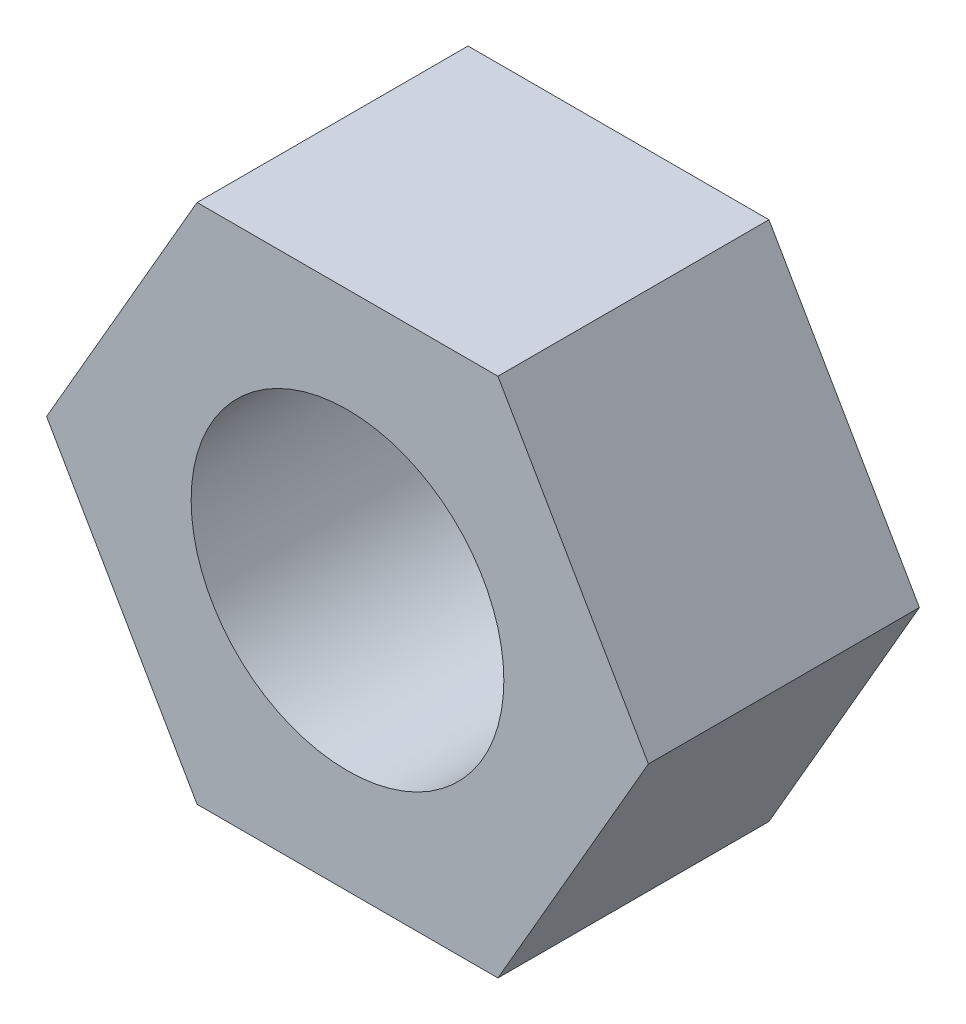
SolidWorks part; units mm, degrees
ref_plane "前视基准面" through (0, 0, 0) normal (0, 0, 1) x (1, 0, 0)
ref_plane "上视基准面" through (0, 0, 0) normal (0, 1, 0) x (1, 0, 0)
ref_plane "右视基准面" through (0, 0, 0) normal (1, 0, 0) x (0, 0, -1)
other "Configuration Table"
sketch "草图1" plane through (0, 0, 0) normal (0, 0, 1) x (1, 0, 0)
  line L0 (5.7735, 0) -> (2.8868, 5)
  line L1 (2.8868, 5) -> (-2.8868, 5)
  line L2 (-2.8868, 5) -> (-5.7735, 0)
  line L3 (-5.7735, 0) -> (-2.8868, -5)
  line L4 (-2.8868, -5) -> (2.8868, -5)
  line L5 (2.8868, -5) -> (5.7735, 0)
  circle A0 centre (0, 0) radius 3
extrude "凸台-拉伸1" add sketch "草图1" against normal blind 5.2
